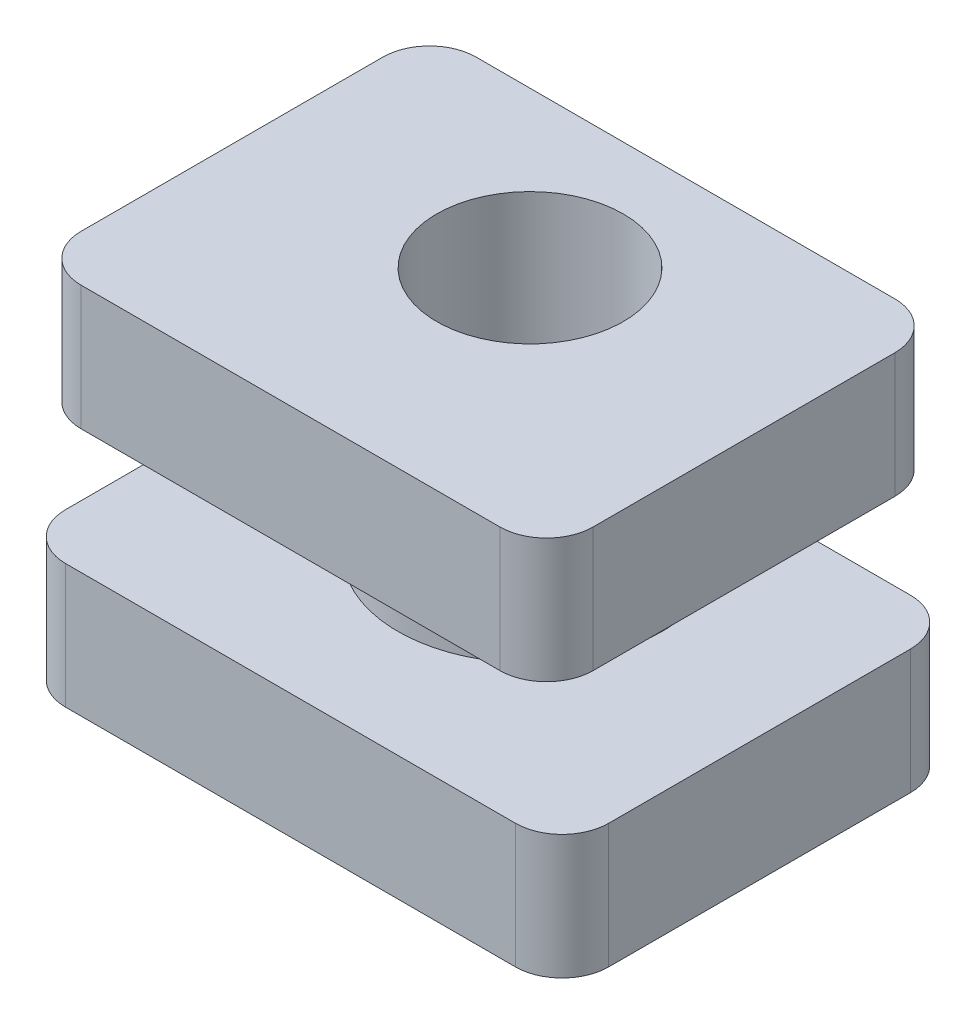
SolidWorks part; units mm, degrees
ref_plane "Front Plane" through (0, 0, 0) normal (0, 0, 1) x (1, 0, 0)
ref_plane "Top Plane" through (0, 0, 0) normal (0, 1, 0) x (1, 0, 0)
ref_plane "Right Plane" through (0, 0, 0) normal (1, 0, 0) x (0, 0, -1)
sketch "Sketch1" plane through (0, 0, 0) normal (0, 1, 0) x (1, 0, 0)
  line L1 (-3.6156, -3.175) -> (3.6156, -3.175)
  line L2 (-4.3656, -2.425) -> (-4.3656, 2.425)
  line L3 (-3.6156, 3.175) -> (3.6156, 3.175)
  line L4 (4.3656, -2.425) -> (4.3656, 2.425)
  line L5 (-4.3656, -3.175) -> (4.3656, 3.175) construction
  line L6 (-4.3656, 3.175) -> (4.3656, -3.175) construction
  arc A0 (-3.6156, 3.175) -> (-4.3656, 2.425) centre (-3.6156, 2.425) ccw
  arc A1 (-4.3656, -2.425) -> (-3.6156, -3.175) centre (-3.6156, -2.425) ccw
  arc A2 (3.6156, -3.175) -> (4.3656, -2.425) centre (3.6156, -2.425) ccw
  arc A3 (4.3656, 2.425) -> (3.6156, 3.175) centre (3.6156, 2.425) ccw
  point P0 (0, 0)
  dimension "D3" = 0.75
  dimension "D1" = 6.35
  dimension "D2" = 8.7312
extrude "Boss-Extrude1" add sketch "Sketch1" along normal blind 2
sketch "Sketch2" plane through (0, 2, 0) normal (0, 1, 0) x (1, 0, 0)
  line L0 (3.6156, 3.175) -> (-3.6156, 3.175) construction
  line L1 (-1.5, 2.175) -> (1.5, 2.175)
  line L2 (-1.5, 2.175) -> (-1.5, 3.175)
  line L3 (-1.5, 3.175) -> (1.5, 3.175)
  line L4 (1.5, 2.175) -> (1.5, 3.175)
  line L5 (-1.5, 2.175) -> (1.5, 3.175) construction
  line L6 (-1.5, 3.175) -> (1.5, 2.175) construction
  circle A0 centre (0, 0.675) radius 2.125
  point P0 (0, 2.675)
  line M11 (3.6156, 3.175) -> (-3.6156, 3.175)
  dimension "D3" = 4.25
  dimension "D4" = 2.5
  dimension "D1" = 1
  dimension "D2" = 3
extrude "Boss-Extrude2" add sketch "Sketch2" along normal blind 2 contours L2 A0 L4 L1 | A0 L4 L2 M11 | L4 A0 L2 L1
sketch "Sketch3" plane through (0, 4, 0) normal (0, 1, 0) x (1, 0, 0)
  line L0 (-4.1156, 2.425) -> (-4.1156, -2.425)
  line L1 (-4.3656, 2.425) -> (-4.3656, -2.425) construction
  line L2 (4.1156, -2.425) -> (4.1156, 2.425)
  line L3 (3.3656, 3.175) -> (-3.3656, 3.175)
  line L4 (0, 0) -> (0, 1.6746) construction
  line L6 (-3.3656, -3.175) -> (3.3656, -3.175)
  arc A0 (-3.3656, -3.175) -> (-4.1156, -2.425) centre (-3.3656, -2.425) cw
  arc A1 (-3.3656, 3.175) -> (-4.1156, 2.425) centre (-3.3656, 2.425) ccw
  arc A2 (3.3656, -3.175) -> (4.1156, -2.425) centre (3.3656, -2.425) ccw
  arc A3 (3.3656, 3.175) -> (4.1156, 2.425) centre (3.3656, 2.425) cw
  dimension "D3" = 0.75
  dimension "D4" = 0.75
  dimension "D1" = 0.25
extrude "Boss-Extrude3" add sketch "Sketch3" along normal blind 2
sketch "Sketch4" plane through (0, 0, 0) normal (0, -1, 0) x (1, 0, 0)
  arc A0 (1.5, -2.1802) -> (-1.5, -2.1802) centre (0, -0.675) ccw construction
  arc A1 (1.5, -2.1802) -> (-1.5, -2.1802) centre (0, -0.675) ccw
  circle A2 centre (0, -0.675) radius 2.125
  circle A3 centre (0, -0.675) radius 1.5
  dimension "D1" = 3
extrude "Cut-Extrude1" cut sketch "Sketch4" against normal through all contours A3
